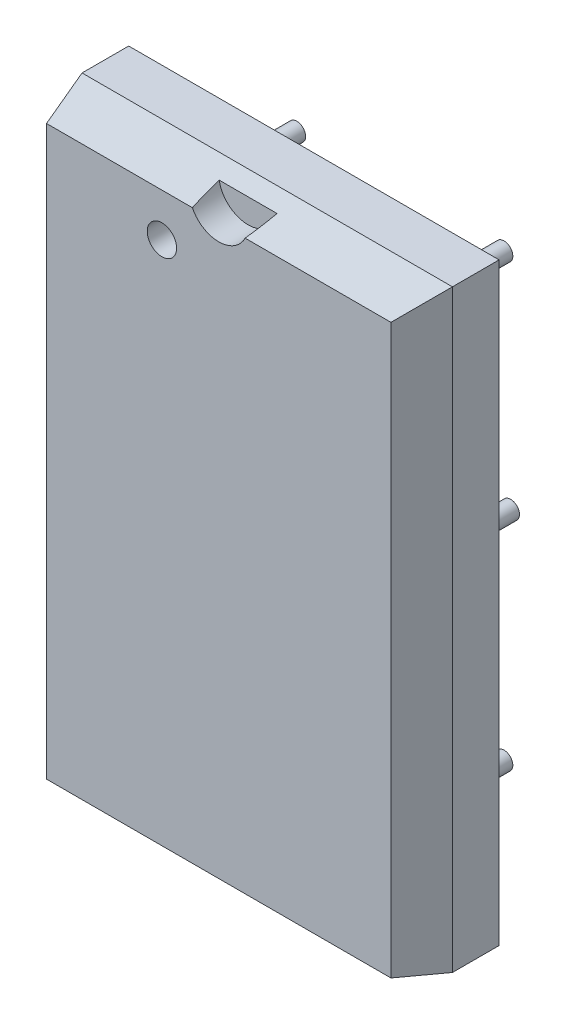
SolidWorks part; units mm, degrees
ref_plane "Спереди" through (0, 0, 0) normal (0, 0, 1) x (1, 0, 0)
ref_plane "Сверху" through (0, 0, 0) normal (0, 1, 0) x (1, 0, 0)
ref_plane "Справа" through (0, 0, 0) normal (1, 0, 0) x (0, 0, -1)
ref_plane "Плоскость1" through (0, 0, 4.32) normal (0, 0, 1) x (1, 0, 0)
sketch "Эскиз2" plane through (0, 0, 4.32) normal (0, 0, 1) x (1, 0, 0)
  line L0 (4.13, 0.5264) -> (4.13, -12.1874) construction
  line L3 (-1.5963, -7.62) -> (10.5039, -7.62) construction
  line L7 (-2.17, 2.48) -> (10.43, 2.48)
  line L8 (-2.17, 2.48) -> (-2.17, -17.72)
  line L9 (-2.17, -17.72) -> (10.43, -17.72)
  line L10 (10.43, 2.48) -> (10.43, -17.72)
  dimension "D1" = 12.6
  dimension "D2" = 20.2
extrude "Вытянуть1" add sketch "Эскиз2" against normal blind 3.68
chamfer "Фаска1" distance 1.65 angle 15 8 edges at (4.13, -17.72, 0.64) (-2.17, -7.62, 0.64) (4.13, 2.48, 0.64) (10.43, -7.62, 0.64) (4.13, -17.72, 4.32) (-2.17, -7.62, 4.32) (4.13, 2.48, 4.32) (10.43, -7.62, 4.32)
sketch "Эскиз6" plane through (0, 0, 4.32) normal (0, 0, 1) x (1, 0, 0)
  line L0 (-2.17, 2.48) -> (10.43, 2.48) construction
  circle A0 centre (4.13, 2.48) radius 1
  circle A1 centre (2.1974, 0.5741) radius 0.5
extrude "Вырез-Вытянуть1" cut sketch "Эскиз6" against normal blind 1
sketch "Эскиз7" plane through (0, 0, 0.64) normal (0, 0, -1) x (-1, 0, 0)
  line L0 (-4.13, 4.8654) -> (-4.13, -18.9717) construction
  line L1 (-12.4638, -7.3749) -> (-12.4944, -7.62) construction
  line L2 (-12.4944, -7.62) -> (5.0004, -7.62) construction
  line L3 (0.52, 0.83) -> (-8.78, 0.83) construction
  line L4 (-8.78, -16.07) -> (0.52, -16.07) construction
  line L5 (0.52, -16.07) -> (0.52, 0.83) construction
  line L6 (-8.78, 0.83) -> (-8.78, -16.07) construction
  circle A0 centre (-7.88, -7.62) radius 0.3
  circle A1 centre (-7.6535, -0.12) radius 0.3
  circle A2 centre (-7.6535, -15.12) radius 0.3
  circle A3 centre (-0.6065, -15.12) radius 0.3
  circle A4 centre (-0.6065, -0.12) radius 0.3
  circle A5 centre (-0.38, -7.62) radius 0.3
  dimension "D1" = 15
  dimension "D2" = 3.75
  dimension "D3" = 0.6
extrude "Вытянуть2" add sketch "Эскиз7" along normal blind 2.5
